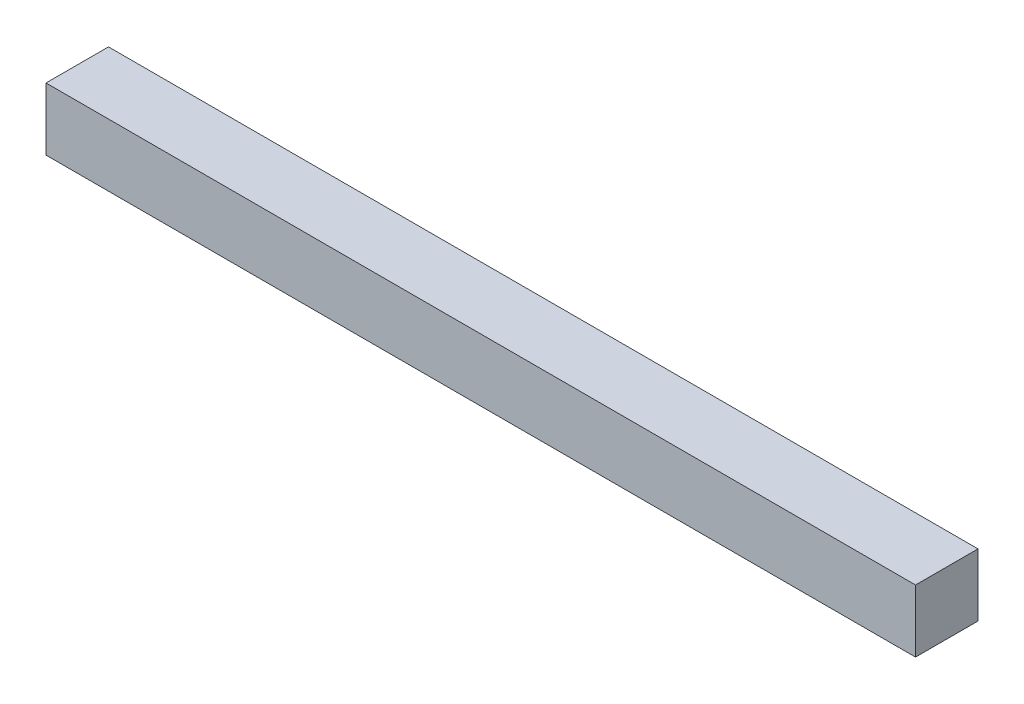
SolidWorks part; units mm, degrees
ref_plane "Спереди" through (0, 0, 0) normal (0, 0, 1) x (1, 0, 0)
ref_plane "Сверху" through (0, 0, 0) normal (0, 1, 0) x (1, 0, 0)
ref_plane "Справа" through (0, 0, 0) normal (1, 0, 0) x (0, 0, -1)
sketch "Эскиз1" plane through (0, 0, 0) normal (1, 0, 0) x (0, 0, -1)
  line L1 (5.6245, 12.2376) -> (-17.3755, 12.2376)
  line L2 (5.6245, 12.2376) -> (5.6245, -10.7624)
  line L3 (5.6245, -10.7624) -> (-17.3755, -10.7624)
  line L4 (-17.3755, 12.2376) -> (-17.3755, -10.7624)
extrude "Бобышка-Вытянуть1" add sketch "Эскиз1" along normal blind 320
